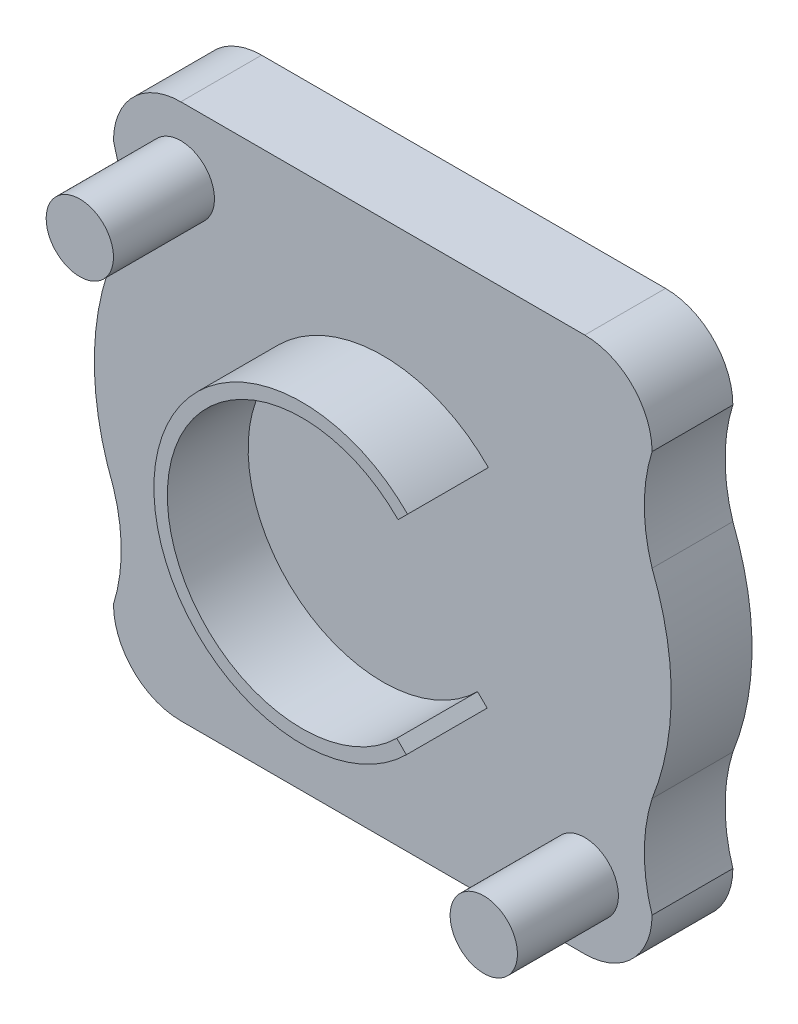
SolidWorks part; units mm, degrees
material "ABS"
ref_plane "Front Plane" through (0, 0, 0) normal (0, 0, 1) x (1, 0, 0)
ref_plane "Top Plane" through (0, 0, 0) normal (0, 1, 0) x (1, 0, 0)
ref_plane "Right Plane" through (0, 0, 0) normal (1, 0, 0) x (0, 0, -1)
sketch "Back Plate" plane through (0, 0, 0) normal (0, 0, 1) x (1, 0, 0)
  line L14 (0, -10.16) -> (7.62, -10.16)
  line L15 (0, -10.16) -> (-7.62, -10.16)
  line L17 (-7.62, 10.0663) -> (7.62, 10.0663)
  line L18 (0, -10.16) -> (0, 10.0663) construction
  arc A14 (10.16, 7.5263) -> (7.62, 10.0663) centre (7.62, 7.5263) ccw
  arc A15 (7.62, -10.16) -> (10.16, -7.62) centre (7.62, -7.62) ccw
  arc A16 (-7.62, -10.16) -> (-10.16, -7.62) centre (-7.62, -7.62) cw
  arc A17 (-10.16, 7.5263) -> (-7.62, 10.0663) centre (-7.62, 7.5263) cw
  arc A18 (-10.16, 7.5263) -> (-10.16, 3.7163) centre (-16.2175, 5.6213) cw
  arc A19 (-10.16, -7.62) -> (-10.16, -3.81) centre (-16.2175, -5.715) ccw
  arc A20 (-10.16, 3.7163) -> (-10.16, -3.81) centre (-0.7226, -0.0468) ccw
  arc A21 (10.16, -7.62) -> (10.16, -3.81) centre (16.2175, -5.715) cw
  arc A22 (10.16, 3.7163) -> (10.16, -3.81) centre (0.7226, -0.0468) cw
  arc A23 (10.16, 7.5263) -> (10.16, 3.7163) centre (16.2175, 5.6213) ccw
  dimension "D1" = 2.54
extrude "Boss-Extrude5" add sketch "Back Plate" against normal blind 3.048
sketch "Inner Circle" plane through (0, 0, 0) normal (0, 0, 1) x (1, 0, 0)
  line L0 (-9.4161, -9.4161) -> (9.4161, 9.3224) construction
  line L1 (9.4161, -9.4161) -> (-9.4161, 9.3224) construction
  line L2 (3.6244, 3.5595) -> (3.9845, 3.9178)
  line L3 (3.9377, -3.9649) -> (3.5776, -3.6066)
  arc A0 (3.9845, 3.9178) -> (3.9377, -3.9649) centre (0, 0) ccw
  arc A1 (-10.16, -7.62) -> (-7.62, -10.16) centre (-7.62, -7.62) ccw construction
  arc A2 (10.16, 7.5263) -> (7.62, 10.0663) centre (7.62, 7.5263) ccw construction
  arc A3 (7.62, -10.16) -> (10.16, -7.62) centre (7.62, -7.62) ccw construction
  arc A4 (-7.62, 10.0663) -> (-10.16, 7.5263) centre (-7.62, 7.5263) ccw construction
  arc A5 (3.6244, 3.5595) -> (3.5776, -3.6066) centre (0, 0) ccw
extrude "Boss-Extrude6" add sketch "Inner Circle" along normal blind 3.048
sketch "Prongs" plane through (0, 0, 0) normal (0, 0, 1) x (1, 0, 0)
  circle A2 centre (-7.62, 7.5263) radius 1.27
  circle A3 centre (7.62, -7.62) radius 1.27
extrude "Boss-Extrude7" add sketch "Prongs" along normal blind 3.81
